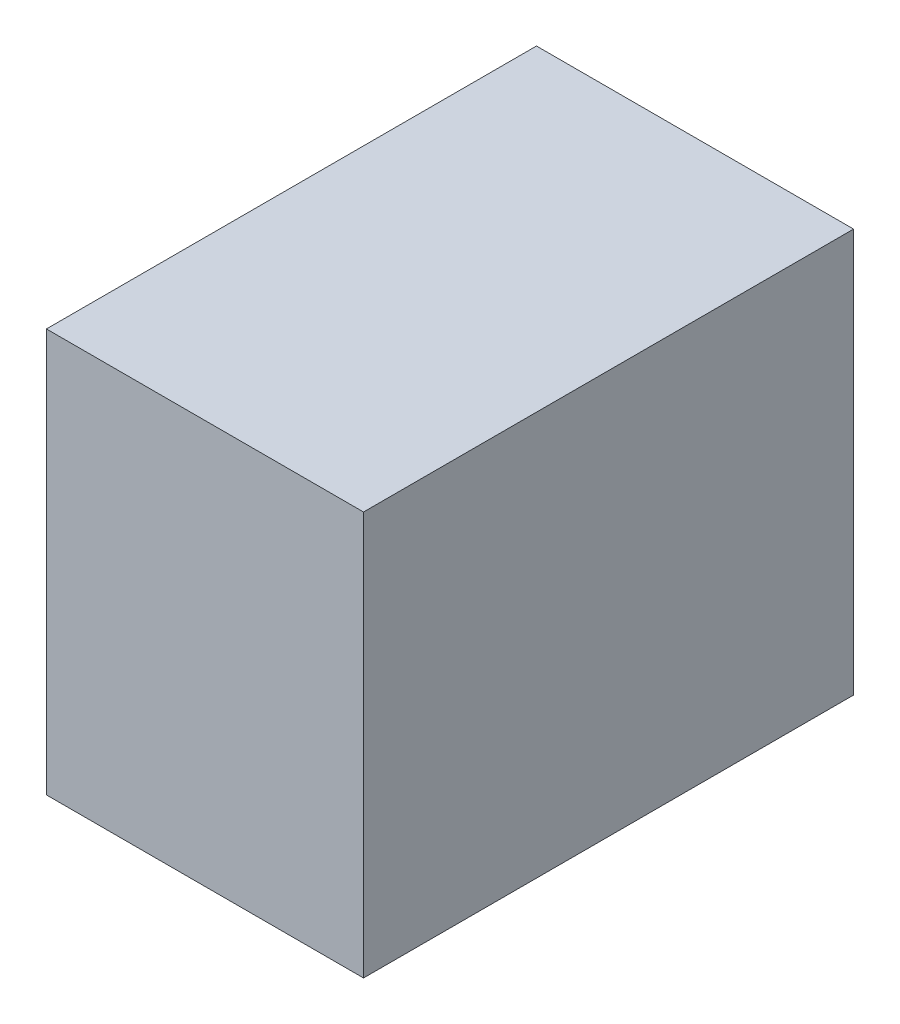
SolidWorks part; units mm, degrees
ref_plane "Front Plane" through (0, 0, 0) normal (0, 0, 1) x (1, 0, 0)
ref_plane "Top Plane" through (0, 0, 0) normal (0, 1, 0) x (1, 0, 0)
ref_plane "Right Plane" through (0, 0, 0) normal (1, 0, 0) x (0, 0, -1)
sketch "Sketch1" plane through (0, 0, 0) normal (0, 1, 0) x (1, 0, 0)
  line L1 (-27.5, -42.5) -> (27.5, -42.5)
  line L2 (-27.5, -42.5) -> (-27.5, 42.5)
  line L3 (-27.5, 42.5) -> (27.5, 42.5)
  line L4 (27.5, -42.5) -> (27.5, 42.5)
  line L5 (-27.5, -42.5) -> (27.5, 42.5) construction
  line L6 (-27.5, 42.5) -> (27.5, -42.5) construction
  point P0 (0, 0)
  dimension "D1" = 55
  dimension "D2" = 85
extrude "Boss-Extrude1" add sketch "Sketch1" along normal blind 70
